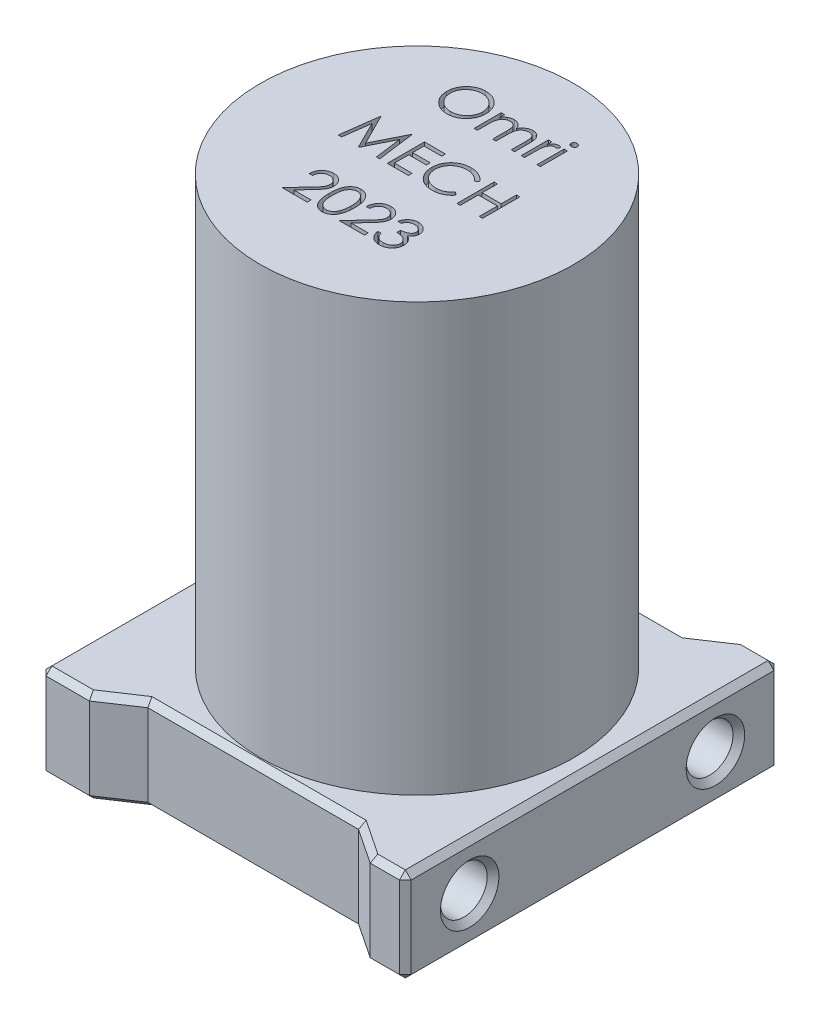
SolidWorks part; units mm, degrees
ref_plane "Front Plane" through (0, 0, 0) normal (0, 0, 1) x (1, 0, 0)
ref_plane "Top Plane" through (0, 0, 0) normal (0, 1, 0) x (1, 0, 0)
ref_plane "Right Plane" through (0, 0, 0) normal (1, 0, 0) x (0, 0, -1)
sketch "Sketch1" plane through (0, 0, 0) normal (0, 1, 0) x (1, 0, 0)
  circle A0 centre (0, 0) radius 13.4
  dimension "D1" = 26.8
extrude "Boss-Extrude1" add sketch "Sketch1" along normal blind 36.5
sketch "Sketch2" plane through (0, 0, 0) normal (0, -1, 0) x (1, 0, 0)
  line L0 (0, 0) -> (27.3656, 0) construction
  line L1 (-16.2, -16) -> (-16.2, 16)
  line L2 (-16.2, 16) -> (15, 16)
  line L3 (15, 16) -> (15, -16)
  line L4 (-16.2, -16) -> (15, -16)
  point P8 (15, 0)
  point P9 (-16.2, 0)
  dimension "D1" = 15
  dimension "D2" = 16.2
  dimension "D3" = 16
extrude "Boss-Extrude3" add sketch "Sketch2" along normal blind 8
hole_wizard "Ø4.0mm Dowel Hole1" positions "Sketch6" profile "Sketch5" hole size "Ø4.0" standard "ANSI Metric"
sketch "Sketch6" plane through (-16.2, 0, 0) normal (-1, 0, 0) x (0, 0, 1)
  line L0 (-16, -8) -> (-16, 0) construction
  line L2 (16, -8) -> (-16, -8) construction
  line L3 (16, -8) -> (16, 0) construction
  point P0 (-10.5, -4)
  point P2 (10.5, -4)
  dimension "D1" = 5.5
  dimension "D2" = 4
  dimension "D3" = 5.5
  dimension "D4" = 4
sketch "Sketch5" plane through (-16.2, -4, -10.5) normal (0, 1, 0) x (0, 0, 1)
  line L0 (0, 0) -> (0, 11.2017)
  line L1 (0, 11.2017) -> (2, 10)
  line L2 (2, 10) -> (2, 0)
  line L5 (2, 0) -> (0, 0)
  line L10 (0, 11.2017) -> (-2, 10) construction
  line L11 (0, -6.35) -> (0, 107.95) construction
  dimension "Hole Dia." = 4
  dimension "Hole Depth" = 10
  dimension "Drill Angle" = 118
hole_wizard "Ø4.0mm Dowel Hole2" positions "Sketch8" profile "Sketch9" hole size "Ø4.0" standard "ANSI Metric"
sketch "Sketch8" plane through (15, 0, 0) normal (1, 0, 0) x (0, 0, -1)
  line L0 (-16, -8) -> (-16, 0) construction
  line L1 (16, -8) -> (-16, -8) construction
  line L2 (16, -8) -> (16, 0) construction
  point P0 (-10.5, -4)
  point P2 (10.5, -4)
  dimension "D1" = 5.5
  dimension "D2" = 4
  dimension "D3" = 5.5
  dimension "D4" = 4
sketch "Sketch9" plane through (15, -4, 10.5) normal (0, 1, 0) x (0, 0, -1)
  line L0 (0, 0) -> (0, 11.2017)
  line L1 (0, 11.2017) -> (2, 10)
  line L2 (2, 10) -> (2, 0)
  line L5 (2, 0) -> (0, 0)
  line L10 (0, 11.2017) -> (-2, 10) construction
  line L11 (0, -6.35) -> (0, 107.95) construction
  dimension "Hole Dia." = 4
  dimension "Hole Depth" = 10
  dimension "Drill Angle" = 118
sketch "Sketch12" plane through (0, 36.5, 0) normal (0, 1, 0) x (1, 0, 0)
  line L0 (-10, 5.8097) -> (10, 5.8097) construction
  text T0 "Omri\r\nMECH\r\n2023"
  dimension "D1" = 20
  dimension "D2" = 10
extrude "Cut-Extrude1" cut sketch "Sketch12" against normal blind 1
sketch "Sketch14" plane through (0, 0, 0) normal (0, 1, 0) x (1, 0, 0)
  line L0 (9, -14) -> (-9, -14)
  line L1 (-9, -14) -> (-12, -16)
  line L2 (15, -16) -> (-16.2, -16) construction
  line L3 (-12, -16) -> (12, -16)
  line L4 (0, -17.6) -> (0, 17.6) construction
  line L5 (9, -14) -> (12, -16)
  line L6 (-17.16, 0) -> (17.16, 0) construction
  line L7 (9, 14) -> (12, 16)
  line L8 (-12, 16) -> (12, 16)
  line L9 (-9, 14) -> (-12, 16)
  line L10 (9, 14) -> (-9, 14)
  point P2 (0, -14.1558)
  point P10 (0, -16)
  point P11 (0, -14)
  dimension "D1" = 12
  dimension "D2" = 9
  dimension "D3" = 2
extrude "Cut-Extrude2" cut sketch "Sketch14" against normal up to surface (8 mm away) up to face at (-0.6, -8, 0)
chamfer "Chamfer2" distance 0.5 angle 45 32 edges at (-14.1, -8, 16) (13.5, -8, 16) (15, -8, 0) (-14.1, -8, -16) (13.5, -8, -16) (-16.2, -8, 0) (13.5, 0, 16) (-14.1, 0, 16) (15, 0, 0) (13.5, 0, -16) (-14.1, 0, -16) (-16.2, 0, 0) (-16.2, -4, 12.5) (-16.2, -4, -8.5) (15, -4, -12.5) (15, -4, 8.5) (-10.5, 0, -15) (0, 0, -14) (10.5, 0, -15) (-10.5, 0, 15) (0, 0, 14) (10.5, 0, 15) (-16.2, -4, 16) (-16.2, -4, -16) (15, -4, -16) (15, -4, 16) (10.5, -8, 15) (10.5, -8, -15) (0, -8, -14) (-10.5, -8, -15) (-10.5, -8, 15) (0, -8, 14)
